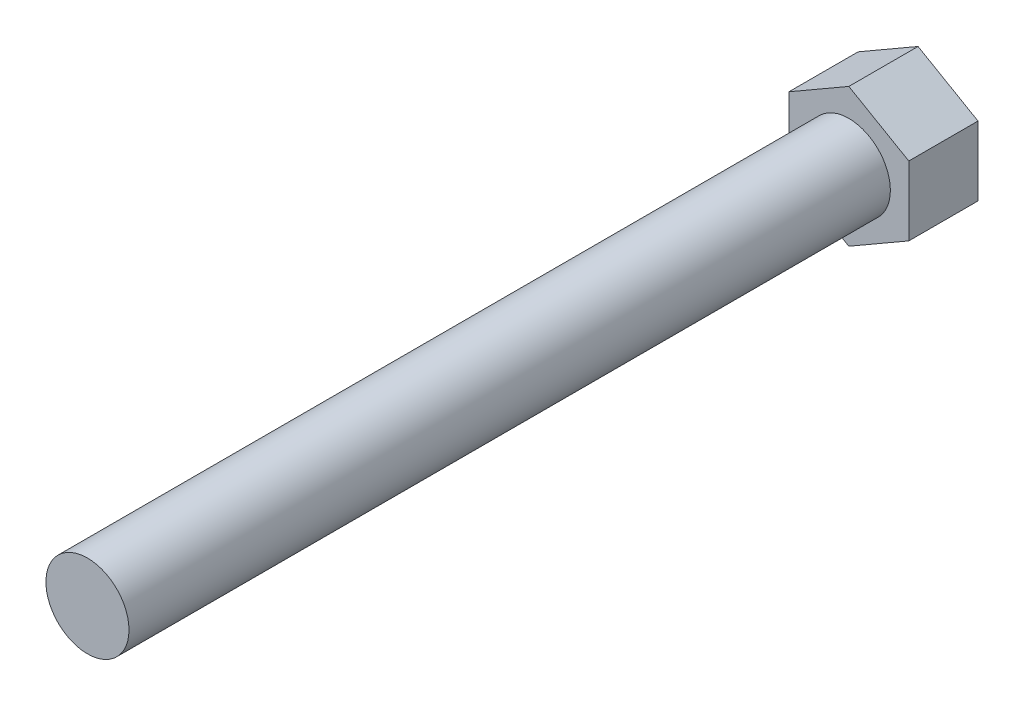
SolidWorks part; units mm, degrees
ref_plane "Front Plane" through (0, 0, 0) normal (0, 0, 1) x (1, 0, 0)
ref_plane "Top Plane" through (0, 0, 0) normal (0, 1, 0) x (1, 0, 0)
ref_plane "Right Plane" through (0, 0, 0) normal (1, 0, 0) x (0, 0, -1)
sketch "Sketch1" plane through (0, 0, 0) normal (0, 0, 1) x (1, 0, 0)
  line L1 (0, 10) -> (-8.6603, 5)
  line L2 (-8.6603, 5) -> (-8.6603, -5)
  line L3 (-8.6603, -5) -> (0, -10)
  line L4 (0, -10) -> (8.6603, -5)
  line L5 (8.6603, -5) -> (8.6603, 5)
  line L6 (8.6603, 5) -> (0, 10)
  circle A0 centre (0, 0) radius 8.6603 construction
  dimension "D1" = 10
extrude "Boss-Extrude1" add sketch "Sketch1" along normal blind 10
sketch "Sketch2" plane through (0, 0, 10) normal (0, 0, 1) x (1, 0, 0)
  circle A0 centre (0, 0) radius 6
  dimension "D1" = 12
extrude "Boss-Extrude2" add sketch "Sketch2" along normal blind 110
